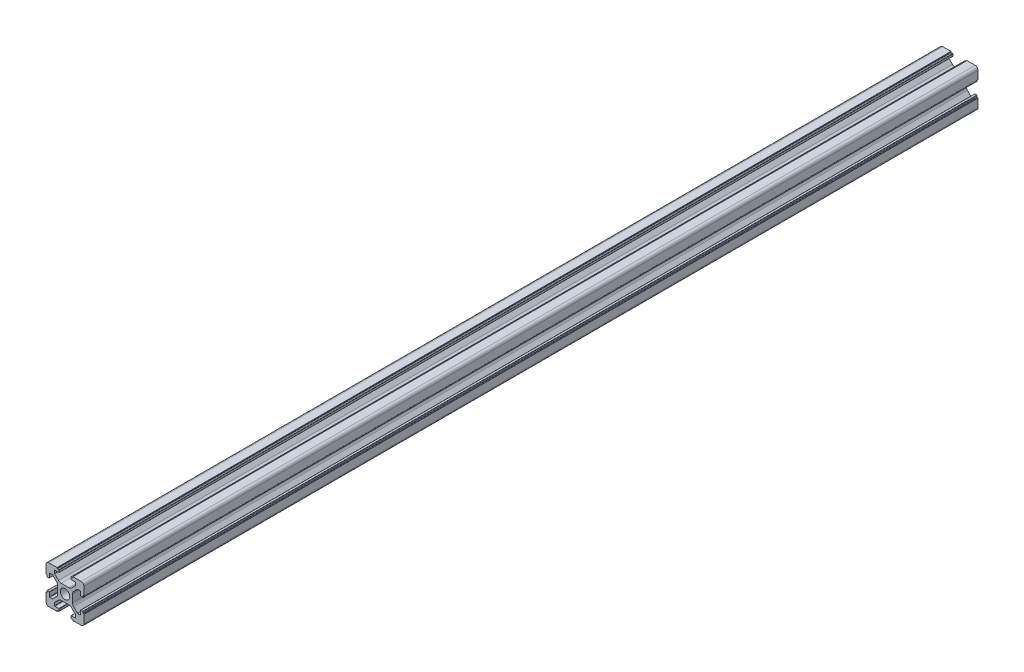
SolidWorks part; units mm, degrees
material "6063-T5"
ref_plane "Front Plane" through (0, 0, 0) normal (0, 0, 1) x (1, 0, 0)
ref_plane "Top Plane" through (0, 0, 0) normal (0, 1, 0) x (1, 0, 0)
ref_plane "Right Plane" through (0, 0, 0) normal (1, 0, 0) x (0, 0, -1)
sketch "Sketch1" plane through (0, 0, 0) normal (0, 0, -1) x (1, 0, 0)
  line L0 (1.5, 0) -> (5.8, 0)
  line L1 (20, 1.5) -> (20, 5.8)
  line L2 (18.5, 20) -> (14.2, 20)
  line L3 (0, 18.5) -> (0, 14.2)
  line L4 (14.2, 0) -> (18.5, 0)
  line L5 (13.3, 18.2) -> (15.3, 18.2)
  line L6 (20, 14.2) -> (20, 18.5)
  line L7 (0, 5.8) -> (0, 1.5)
  line L8 (6.7, 18.2) -> (4.7, 18.2)
  line L9 (1.8, 13.3) -> (1.8, 15.3)
  line L10 (19.3, 13.1) -> (18.4, 13.1)
  line L11 (19.3, 6.9) -> (18.4, 6.9)
  line L12 (6.9, 19.3) -> (6.9, 18.4)
  line L13 (13.1, 19.3) -> (13.1, 18.4)
  line L14 (0.7, 13.1) -> (1.6, 13.1)
  line L15 (0.7, 6.9) -> (1.6, 6.9)
  line L16 (13.4251, 14.4858) -> (15.4121, 16.4728)
  line L17 (14.4858, 13.4251) -> (16.4728, 15.4121)
  line L18 (14.4858, 6.5749) -> (16.4728, 4.5879)
  line L19 (13.4251, 5.5142) -> (15.4121, 3.5272)
  line L20 (6.5749, 5.5142) -> (4.5879, 3.5272)
  line L21 (5.5142, 6.5749) -> (3.5272, 4.5879)
  line L22 (5.5142, 13.4251) -> (3.5272, 15.4121)
  line L23 (6.5749, 14.4858) -> (4.5879, 16.4728)
  line L24 (6.9, 0.7) -> (6.9, 1.6)
  line L25 (13.1, 0.7) -> (13.1, 1.6)
  line L26 (5.8, 20) -> (1.5, 20)
  line L27 (1.8, 6.7) -> (1.8, 4.7)
  line L28 (6.7, 1.8) -> (4.7, 1.8)
  line L29 (13.3, 1.8) -> (15.3, 1.8)
  line L30 (18.2, 13.3) -> (18.2, 15.3)
  line L31 (18.2, 6.7) -> (18.2, 4.7)
  line L32 (2, 4.5) -> (3.3151, 4.5)
  line L33 (2, 15.5) -> (3.3151, 15.5)
  line L34 (4.5, 18) -> (4.5, 16.6849)
  line L35 (15.5, 18) -> (15.5, 16.6849)
  line L36 (18, 15.5) -> (16.6849, 15.5)
  line L37 (4.5, 2) -> (4.5, 3.3151)
  line L38 (15.5, 2) -> (15.5, 3.3151)
  line L39 (18, 4.5) -> (16.6849, 4.5)
  line L40 (7.9891, 13.9) -> (12.0109, 13.9)
  line L41 (7.9891, 6.1) -> (12.0109, 6.1)
  line L42 (13.9, 12.0109) -> (13.9, 7.9891)
  line L43 (6.1, 12.0109) -> (6.1, 7.9891)
  line L44 (19.5, 6.7) -> (19.5, 6.1)
  line L45 (5.9, 19.9) -> (5.9, 19.7)
  line L46 (6.1, 19.5) -> (6.7, 19.5)
  line L47 (14.1, 19.9) -> (14.1, 19.7)
  line L48 (13.9, 19.5) -> (13.3, 19.5)
  line L49 (0.1, 14.1) -> (0.3, 14.1)
  line L50 (0.5, 13.9) -> (0.5, 13.3)
  line L51 (0.1, 5.9) -> (0.3, 5.9)
  line L52 (0.5, 6.1) -> (0.5, 6.7)
  line L53 (19.9, 14.1) -> (19.7, 14.1)
  line L54 (19.5, 13.9) -> (19.5, 13.3)
  line L55 (19.7, 5.9) -> (19.9, 5.9)
  line L56 (14.1, 0.1) -> (14.1, 0.3)
  line L57 (13.9, 0.5) -> (13.3, 0.5)
  line L58 (6.7, 0.5) -> (6.1, 0.5)
  line L59 (5.9, 0.3) -> (5.9, 0.1)
  circle A0 centre (10, 10) radius 2.5
  arc A1 (18.5, 0) -> (20, 1.5) centre (18.5, 1.5) ccw
  arc A2 (1.5, 0) -> (0, 1.5) centre (1.5, 1.5) cw
  arc A3 (20, 18.5) -> (18.5, 20) centre (18.5, 18.5) ccw
  arc A4 (1.5, 20) -> (0, 18.5) centre (1.5, 18.5) ccw
  arc A5 (12.0109, 6.1) -> (13.4251, 5.5142) centre (12.0109, 4.1) cw
  arc A6 (13.9, 7.9891) -> (14.4858, 6.5749) centre (15.9, 7.9891) ccw
  arc A7 (13.9, 12.0109) -> (14.4858, 13.4251) centre (15.9, 12.0109) cw
  arc A8 (12.0109, 13.9) -> (13.4251, 14.4858) centre (12.0109, 15.9) ccw
  arc A9 (7.9891, 13.9) -> (6.5749, 14.4858) centre (7.9891, 15.9) cw
  arc A10 (6.1, 7.9891) -> (5.5142, 6.5749) centre (4.1, 7.9891) cw
  arc A11 (6.1, 12.0109) -> (5.5142, 13.4251) centre (4.1, 12.0109) ccw
  arc A12 (13.1, 1.6) -> (13.3, 1.8) centre (13.3, 1.6) cw
  arc A13 (6.9, 1.6) -> (6.7, 1.8) centre (6.7, 1.6) ccw
  arc A14 (6.1, 0.5) -> (5.9, 0.3) centre (6.1, 0.3) ccw
  arc A15 (6.7, 0.5) -> (6.9, 0.7) centre (6.7, 0.7) ccw
  arc A16 (1.6, 6.9) -> (1.8, 6.7) centre (1.6, 6.7) cw
  arc A17 (0.5, 6.7) -> (0.7, 6.9) centre (0.7, 6.7) cw
  arc A18 (0.5, 13.3) -> (0.7, 13.1) centre (0.7, 13.3) ccw
  arc A19 (1.6, 13.1) -> (1.8, 13.3) centre (1.6, 13.3) ccw
  arc A20 (6.7, 19.5) -> (6.9, 19.3) centre (6.7, 19.3) cw
  arc A21 (6.9, 18.4) -> (6.7, 18.2) centre (6.7, 18.4) cw
  arc A22 (13.1, 18.4) -> (13.3, 18.2) centre (13.3, 18.4) ccw
  arc A23 (13.3, 19.5) -> (13.1, 19.3) centre (13.3, 19.3) ccw
  arc A24 (18.4, 13.1) -> (18.2, 13.3) centre (18.4, 13.3) cw
  arc A25 (19.5, 13.3) -> (19.3, 13.1) centre (19.3, 13.3) cw
  arc A26 (19.5, 6.7) -> (19.3, 6.9) centre (19.3, 6.7) ccw
  arc A27 (14.1, 0.3) -> (13.9, 0.5) centre (13.9, 0.3) ccw
  arc A28 (19.5, 6.1) -> (19.7, 5.9) centre (19.7, 6.1) ccw
  arc A29 (5.9, 19.7) -> (6.1, 19.5) centre (6.1, 19.7) ccw
  arc A30 (14.1, 19.7) -> (13.9, 19.5) centre (13.9, 19.7) cw
  arc A31 (19.7, 14.1) -> (19.5, 13.9) centre (19.7, 13.9) ccw
  arc A32 (13.3, 0.5) -> (13.1, 0.7) centre (13.3, 0.7) cw
  arc A33 (0.3, 14.1) -> (0.5, 13.9) centre (0.3, 13.9) cw
  arc A34 (0.3, 5.9) -> (0.5, 6.1) centre (0.3, 6.1) ccw
  arc A35 (0, 5.8) -> (0.1, 5.9) centre (0.1, 5.8) cw
  arc A36 (5.9, 0.1) -> (5.8, 0) centre (5.8, 0.1) cw
  arc A37 (14.1, 0.1) -> (14.2, 0) centre (14.2, 0.1) ccw
  arc A38 (19.9, 5.9) -> (20, 5.8) centre (19.9, 5.8) cw
  arc A39 (20, 14.2) -> (19.9, 14.1) centre (19.9, 14.2) cw
  arc A40 (14.2, 20) -> (14.1, 19.9) centre (14.2, 19.9) ccw
  arc A41 (5.8, 20) -> (5.9, 19.9) centre (5.8, 19.9) cw
  arc A42 (0, 14.2) -> (0.1, 14.1) centre (0.1, 14.2) ccw
  arc A43 (18.4, 6.9) -> (18.2, 6.7) centre (18.4, 6.7) ccw
  arc A44 (1.8, 15.3) -> (2, 15.5) centre (2, 15.3) cw
  arc A45 (1.8, 4.7) -> (2, 4.5) centre (2, 4.7) ccw
  arc A46 (4.7, 1.8) -> (4.5, 2) centre (4.7, 2) cw
  arc A47 (15.3, 1.8) -> (15.5, 2) centre (15.3, 2) ccw
  arc A48 (18.2, 4.7) -> (18, 4.5) centre (18, 4.7) cw
  arc A49 (18.2, 15.3) -> (18, 15.5) centre (18, 15.3) ccw
  arc A50 (15.3, 18.2) -> (15.5, 18) centre (15.3, 18) cw
  arc A51 (4.7, 18.2) -> (4.5, 18) centre (4.7, 18) ccw
  arc A52 (7.9891, 6.1) -> (6.5749, 5.5142) centre (7.9891, 4.1) ccw
  arc A53 (3.3151, 15.5) -> (3.5272, 15.4121) centre (3.3151, 15.2) cw
  arc A54 (4.5, 16.6849) -> (4.5879, 16.4728) centre (4.8, 16.6849) ccw
  arc A55 (15.5, 16.6849) -> (15.4121, 16.4728) centre (15.2, 16.6849) cw
  arc A56 (16.6849, 15.5) -> (16.4728, 15.4121) centre (16.6849, 15.2) ccw
  arc A57 (16.6849, 4.5) -> (16.4728, 4.5879) centre (16.6849, 4.8) cw
  arc A58 (15.5, 3.3151) -> (15.4121, 3.5272) centre (15.2, 3.3151) ccw
  arc A59 (4.5, 3.3151) -> (4.5879, 3.5272) centre (4.8, 3.3151) cw
  arc A60 (3.3151, 4.5) -> (3.5272, 4.5879) centre (3.3151, 4.8) ccw
  point P67 (0, 0)
  point P125 (14.1, 19.5)
extrude "Boss-Extrude1" add sketch "Sketch1" along normal blind 470 contours L23 A54 L34 A51 L8 A21 L12 A20 L46 A29 L45 A41 L26 A4 L3 A42 L49 A33 L50 A18 L14 A19 L9 A44 L33 A53 L22 A11 L43 A10 L21 A60 L32 A45 L27 A16 L15 A17 L52 A34 L51 A35 L7 A2 L0 A36 L59 A14 L58 A15 L24 A13 L28 A46 L37 A59 L20 A52 L41 A5 L19 A58 L38 A47 L29 A12 L25 A32 L57 A27 L56 A37 L4 A1 L1 A38 L55 A28 L44 A26 L11 A43 L31 A48 L39 A57 L18 A6 L42 A7 L17 A56 L36 A49 L30 A24 L10 A25 L54 A31 L53 A39 L6 A3 L2 A40 L47 A30 L48 A23 L13 A22 L5 A50 L35 A55 L16 A8 L40 A9 | A0
